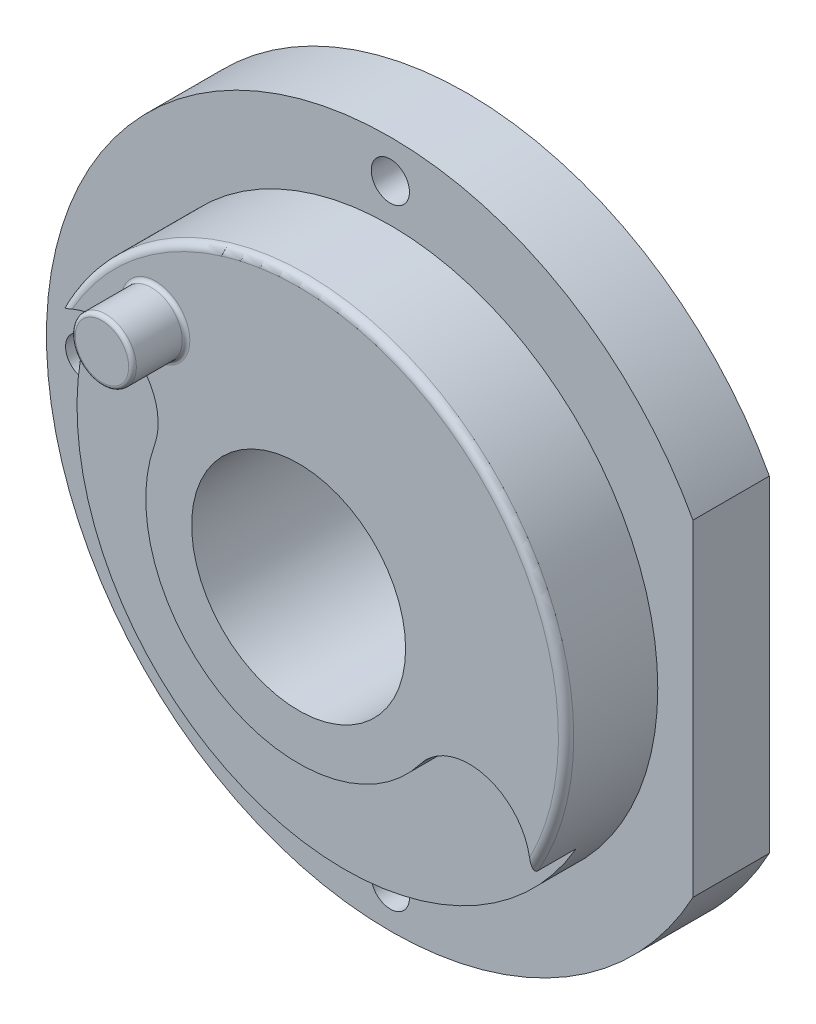
SolidWorks part; units mm, degrees
ref_plane "前视基准面" through (0, 0, 0) normal (0, 0, 1) x (1, 0, 0)
ref_plane "上视基准面" through (0, 0, 0) normal (0, 1, 0) x (1, 0, 0)
ref_plane "右视基准面" through (0, 0, 0) normal (1, 0, 0) x (0, 0, -1)
sketch "草图1" plane through (0, 0, 0) normal (0, 0, 1) x (1, 0, 0)
  circle A0 centre (0, 0) radius 20 construction
  circle A1 centre (0, 0) radius 22.5
  circle A2 centre (0, 20) radius 1.25
  circle A3 centre (0, -20) radius 1.25
  circle A5 centre (-20, 0) radius 1.25
  dimension "D1" = 40
  dimension "D2" = 45
  dimension "D3" = 2.5
  dimension "D4" = 2.5
extrude "凸台-拉伸1" add sketch "草图1" along normal blind 5
sketch "草图2" plane through (0, 0, 5) normal (0, 0, 1) x (1, 0, 0)
  circle A0 centre (0, 0) radius 17.5
  dimension "D1" = 35
extrude "凸台-拉伸2" add sketch "草图2" along normal blind 6
sketch "草图3" plane through (0, 0, 11) normal (0, 0, 1) x (1, 0, 0)
  line L0 (0, 0) -> (-4.6023, 0) construction
  line L1 (0, 0) -> (-9.3678, 10.404) construction
  circle A0 centre (0, 0) radius 14 construction
  circle A1 centre (-9.3678, 10.404) radius 2
  dimension "D1" = 28
  dimension "D2" = 4
  dimension "D3" = 48
extrude "凸台-拉伸3" add sketch "草图3" along normal blind 3.5
fillet "圆角1" radius 0.5 1 edges at (17.5, 0, 11)
fillet "圆角2" radius 0.25 2 edges at (-7.3678, 10.404, 11) (-7.3678, 10.404, 14.5)
sketch "草图4" plane through (0, 0, 11) normal (0, 0, 1) x (1, 0, 0)
  line L0 (-11.3299, 8.224) -> (0, 0) construction
  line L1 (0, 0) -> (13.0988, -4.9417) construction
  circle A0 centre (0, 0) radius 14 construction
  arc A1 (11.1668, -8.4441) -> (-13.193, 4.6844) centre (0, 0) cw construction
  arc A2 (-16.9625, 6.0228) -> (14.3573, -10.8567) centre (0, 0) ccw
  arc A3 (-9.4236, 3.346) -> (7.9763, -6.0315) centre (0, 0) ccw
  arc A4 (-9.4236, 3.346) -> (-16.9625, 6.0228) centre (-13.193, 4.6844) ccw
  arc A5 (14.3573, -10.8567) -> (7.9763, -6.0315) centre (11.1668, -8.4441) ccw
  point P5 (-6.642, -12.3241)
  point P10 (-11.3299, 8.224)
  point P12 (13.0988, -4.9417)
  dimension "D1" = 28
  dimension "D2" = 4
extrude "切除-拉伸1" cut sketch "草图4" against normal blind 3
sketch "草图5" plane through (0, 0, 11) normal (0, 0, 1) x (1, 0, 0)
  circle A0 centre (0, 0) radius 7
  dimension "D1" = 14
extrude "切除-拉伸2" cut sketch "草图5" against normal blind 11
sketch "草图6" plane through (0, 0, 5) normal (0, 0, 1) x (1, 0, 0)
  line L1 (19.8, -17.9414) -> (30.0832, -17.9414)
  line L2 (19.8, -17.9414) -> (19.8, 16.0471)
  line L3 (19.8, 16.0471) -> (30.0832, 16.0471)
  line L4 (30.0832, -17.9414) -> (30.0832, 16.0471)
  circle A0 centre (0, 0) radius 7 construction
  dimension "D1" = 19.8
extrude "切除-拉伸3" cut sketch "草图6" against normal blind 17
